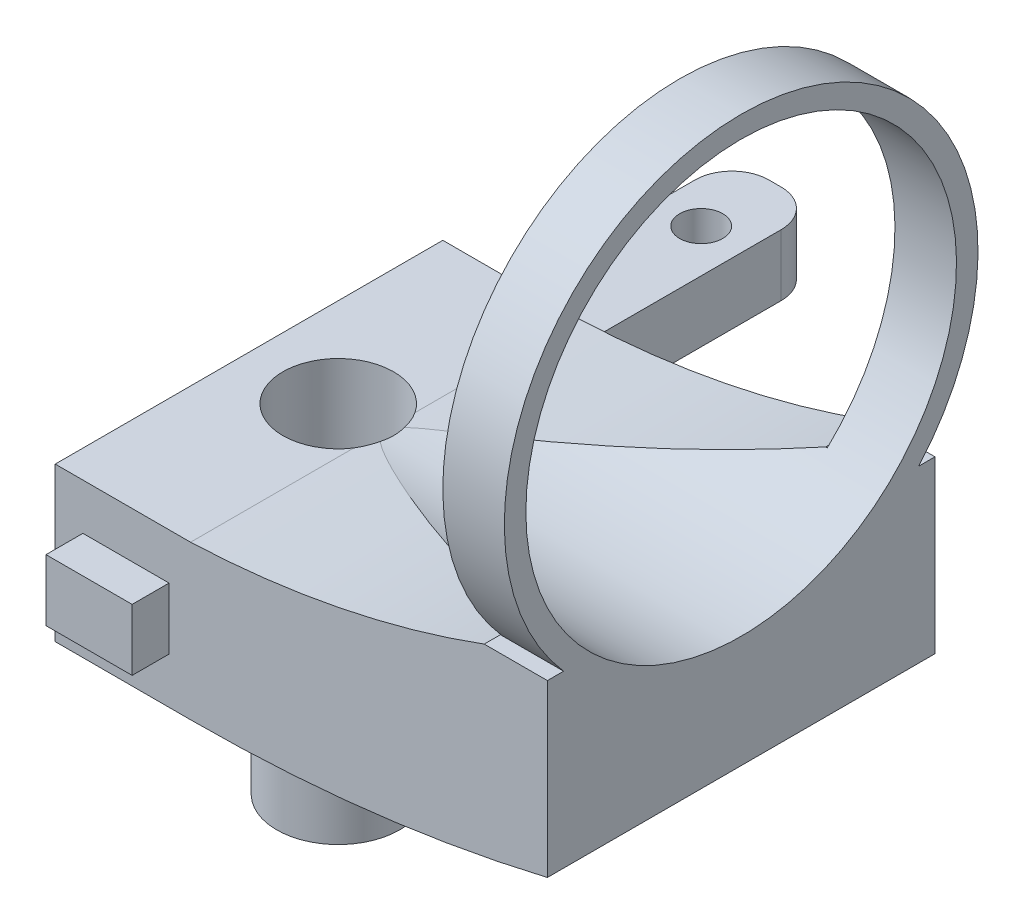
SolidWorks part; units mm, degrees
material "Cast Alloy Steel"
ref_plane "Front Plane" through (0, 0, 0) normal (0, 0, 1) x (1, 0, 0)
ref_plane "Top Plane" through (0, 0, 0) normal (0, 1, 0) x (1, 0, 0)
ref_plane "Right Plane" through (0, 0, 0) normal (1, 0, 0) x (0, 0, -1)
sketch "Sketch1" plane through (0, 0, 0) normal (0, 0, 1) x (1, 0, 0)
  line L0 (0, 0) -> (0, 25.0004)
  line L1 (0, 25.0004) -> (22, 25.0004)
  line L3 (22, 0) -> (0, 0)
  line L4 (0, 25.0004) -> (0, -234) construction
  line L8 (80, 38.7514) -> (80, 6.7987)
  arc A0 (22, 25.0004) -> (80, 38.7514) centre (15.9028, 179.9111) ccw
  arc A1 (22, 0) -> (80, 6.7987) centre (22, 250.8008) ccw
  dimension "D1" = 22
  dimension "D2" = 80
  dimension "D3" = 22
extrude "Boss-Extrude1" add sketch "Sketch1" along normal blind 48
sketch "Sketch2" plane through (0, 0, 48) normal (0, 0, 1) x (1, 0, 0)
  line L0 (0, 0) -> (0, 7.5) construction
  line L1 (0, 25.0004) -> (0, 0) construction
  line L2 (0, 7.5) -> (4.5, 7.5) construction
  line L3 (4.5, 7.5) -> (4.5, 17.5)
  line L4 (4.5, 17.5) -> (18.5, 17.5)
  line L5 (18.5, 17.5) -> (18.5, 7.5)
  line L6 (4.5, 7.5) -> (18.5, 7.5)
  dimension "D1" = 14
  dimension "D2" = 10
  dimension "D3" = 4.5
extrude "Boss-Extrude2" add sketch "Sketch2" along normal blind 50
ref_plane "Plane1" through (0, 0, 24) normal (0, 0, 1) x (1, 0, 0)
sketch "Sketch4" plane through (0, 17.5, 0) normal (0, 1, 0) x (1, 0, 0)
  line L0 (11.5, -48) -> (11.5, -86)
  line L1 (18.5, -48) -> (4.5, -48) construction
hole_wizard "M8x1.0 Tapped Hole1" positions "3DSketch1" profile "Sketch5" tap size "M8x1.0" standard "ANSI Metric"
sketch3d "3DSketch1"
  point P0 (11.5, 17.5, 86)
sketch "Sketch5" plane through (11.5, 17.5, 86) normal (1, 0, 0) x (0, 0, 1)
  line L0 (0, 0) -> (0, 12.103)
  line L1 (0, 12.103) -> (3.5, 10)
  line L2 (3.5, 10) -> (3.5, 0)
  line L5 (3.5, 0) -> (0, 0)
  line L10 (0, 12.103) -> (-3.5, 10) construction
  line L11 (0, -6.35) -> (0, 107.95) construction
  dimension "Tap Drill Dia." = 7
  dimension "Tap Drill Depth" = 10
  dimension "Drill Angle" = 118
cosmetic thread "Hole Thread1" parameters "D1"=10, "D2"=8
fillet "Fillet1" radius 6 2 edges at (4.5, 12.5, 98) (18.5, 12.5, 98)
ref_plane "Plane2" through (80, 0, 0) normal (-1, 0, 0) x (0, 0, 1)
sketch "Sketch7" plane through (80, 0, 0) normal (-1, 0, 0) x (0, 0, 1)
  line L0 (24, 25.0004) -> (24, 60.0004) construction
  line L1 (48, 25.0004) -> (0, 25.0004) construction
  circle A0 centre (24, 60.0004) radius 35
  circle A1 centre (24, 60.0004) radius 38.5
extrude "Boss-Extrude3" add sketch "Sketch7" along normal blind 10
sketch "Sketch8" plane through (80, 0, 0) normal (-1, 0, 0) x (0, 0, 1)
  circle A0 centre (24, 60.0004) radius 35
extrude "Cut-Extrude2" cut sketch "Sketch8" along normal blind 90
sketch "Sketch10" plane through (0, 0, 0) normal (0, -1, 0) x (1, 0, 0)
  line L0 (0, 24) -> (14.5, 24) construction
  line L1 (0, 48) -> (0, 0) construction
  circle A0 centre (14.5, 24) radius 12
  circle A1 centre (14.5, 24) radius 9
extrude "Boss-Extrude4" add sketch "Sketch10" along normal blind 5 and the other way blind 10
sketch "Sketch11" plane through (0, -5, 0) normal (0, -1, 0) x (1, 0, 0)
  circle A0 centre (14.5, 24) radius 10
  circle A1 centre (14.5, 24) radius 9
extrude "Boss-Extrude5" add sketch "Sketch11" along normal blind 25
sketch "Sketch12" plane through (0, 0, 0) normal (0, -1, 0) x (-1, 0, 0)
  circle A0 centre (-14.5, -24) radius 9
extrude "Cut-Extrude3" cut sketch "Sketch12" against normal blind 42
sketch "Sketch13" plane through (0, 0, 48) normal (0, 0, 1) x (1, 0, 0)
  line L0 (0, 25.0004) -> (0, 0)
  line L1 (0, 0) -> (22, 0)
  line L2 (0, 25.0004) -> (22, 25.0004)
  line L3 (69.7299, 34.5249) -> (70, 34.5249)
  line L6 (80, 29.8964) -> (80, 6.7987)
  line L10 (70, 34.5249) -> (80, 34.5249)
  line L11 (80, 29.8964) -> (80, 98.5004) construction
  line L12 (80, 34.5249) -> (80, 29.8964)
  arc A0 (22, 0) -> (80, 6.7987) centre (22, 250.8008) ccw construction
  arc A1 (22, 25.0004) -> (69.7299, 34.5249) centre (15.9028, 179.9111) ccw
  arc A2 (22, 0) -> (80, 6.7987) centre (22, 250.8008) ccw
extrude "Boss-Extrude6" add sketch "Sketch13" along normal blind 7.5
sketch "Sketch14" plane through (0, 0, 0) normal (0, 0, -1) x (-1, 0, 0)
  line L0 (-80, 29.8964) -> (-80, 6.7987)
  line L1 (-22, 0) -> (0, 0)
  line L2 (0, 0) -> (0, 25.0004)
  line L3 (0, 25.0004) -> (-22, 25.0004)
  line L4 (-69.7299, 34.5249) -> (-70, 34.5249)
  line L7 (-70, 34.5249) -> (-80, 34.5249)
  line L8 (-80, 98.5004) -> (-80, 29.8964) construction
  line L9 (-80, 34.5249) -> (-80, 29.8964)
  arc A0 (-80, 6.7987) -> (-22, 0) centre (-22, 250.8008) ccw
  arc A1 (-22, 25.0004) -> (-69.7299, 34.5249) centre (-15.9028, 179.9111) cw
extrude "Boss-Extrude7" add sketch "Sketch14" along normal blind 7.5
mirror "Mirror1" about plane through (0, 0, 24) normal (0, 0, 1) of "Fillet1", "M8x1.0 Tapped Hole1", "Boss-Extrude2"
ref_plane "Plane3" through (0, 0, 61.5) normal (0, 0, 1) x (1, 0, 0)
sketch "Sketch15" plane through (0, 0, 61.5) normal (0, 0, 1) x (1, 0, 0)
  line L1 (4.5, 7.5) -> (18.5, 7.5)
  line L2 (4.5, 7.5) -> (4.5, 17.5)
  line L3 (4.5, 17.5) -> (18.5, 17.5)
  line L4 (18.5, 7.5) -> (18.5, 17.5)
extrude "Cut-Extrude4" cut sketch "Sketch15" along normal blind 101
